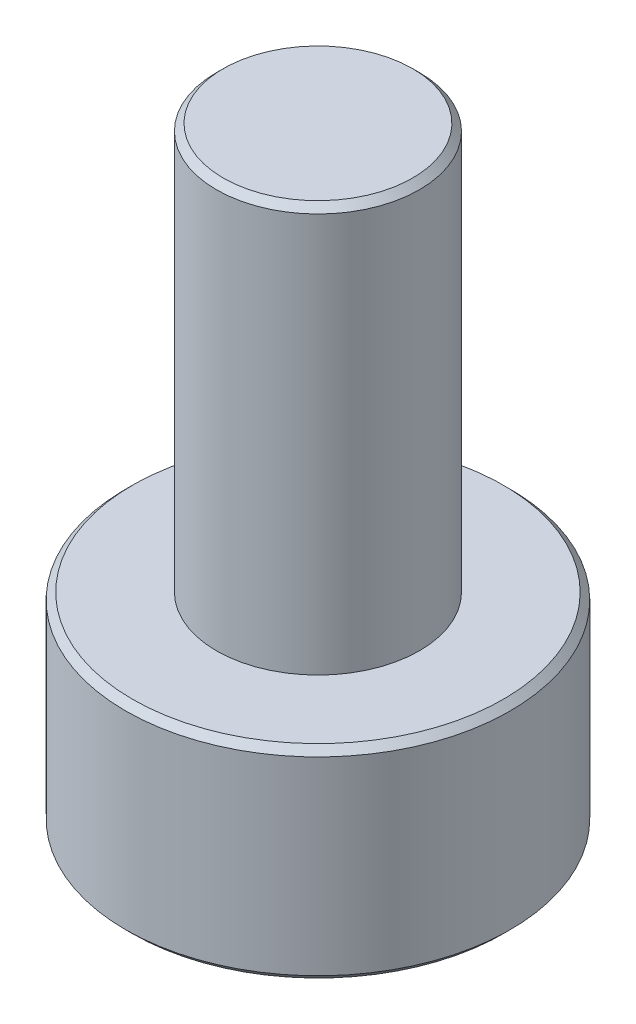
SolidWorks part; units mm, degrees
material "6061 合金"
ref_plane "前视基准面" through (0, 0, 0) normal (0, 0, 1) x (1, 0, 0)
ref_plane "上视基准面" through (0, 0, 0) normal (0, 1, 0) x (1, 0, 0)
ref_plane "右视基准面" through (0, 0, 0) normal (1, 0, 0) x (0, 0, -1)
sketch "草图1" plane through (0, 0, 0) normal (0, 1, 0) x (1, 0, 0)
  circle A0 centre (0, 0) radius 2.84
  dimension "D1" = 5.68
extrude "杯头部分" add sketch "草图1" along normal blind 3
sketch "草图2" plane through (0, 3, 0) normal (0, 1, 0) x (1, 0, 0)
  circle A0 centre (0, 0) radius 1.5
  dimension "D1" = 3
extrude "螺柱部分" add sketch "草图2" along normal blind 6
cosmetic thread "装饰螺纹线1" parameters "D2"=2.459
sketch "草图3" plane through (0, 0, 0) normal (0, -1, 0) x (1, 0, 0)
  line L1 (1.29, -0.7448) -> (1.29, 0.7448)
  line L2 (1.29, 0.7448) -> (0, 1.4896)
  line L3 (0, 1.4896) -> (-1.29, 0.7448)
  line L4 (-1.29, 0.7448) -> (-1.29, -0.7448)
  line L5 (-1.29, -0.7448) -> (0, -1.4896)
  line L6 (0, -1.4896) -> (1.29, -0.7448)
  circle A0 centre (0, 0) radius 1.29 construction
  dimension "D1" = 2.58
extrude "沉头内六角" cut sketch "草图3" against normal blind 1.3
chamfer "修饰性倒角" distance 0.1 angle 45 3 edges at (0, 9, 1.5) (0, 3, 2.84) (0, 0, 2.84)
